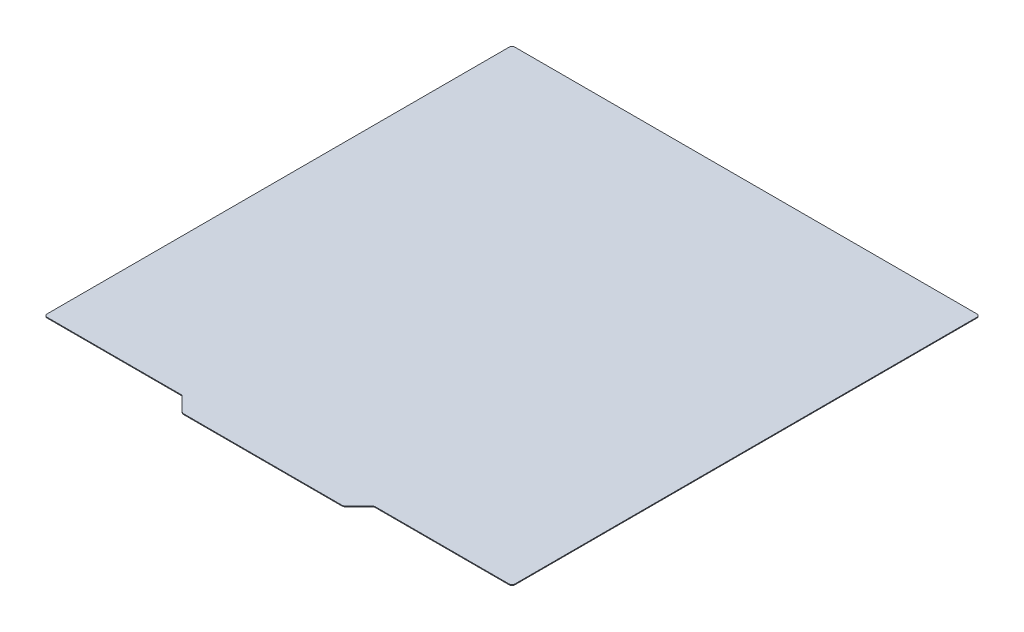
SolidWorks part; units mm, degrees
material "AISI Type 316L stainless steel"
ref_plane "Front Plane" through (0, 0, 0) normal (0, 0, 1) x (1, 0, 0)
ref_plane "Top Plane" through (0, 0, 0) normal (0, 1, 0) x (1, 0, 0)
ref_plane "Right Plane" through (0, 0, 0) normal (1, 0, 0) x (0, 0, -1)
sketch "Sketch1" plane through (0, 0, 0) normal (0, 1, 0) x (1, 0, 0)
  line L0 (-52.5, -162.5) -> (52.5, -162.5)
  line L1 (152.5, -152.5) -> (62.5, -152.5)
  line L2 (152.5, -152.5) -> (152.5, 152.5)
  line L3 (152.5, 152.5) -> (-152.5, 152.5)
  line L4 (-152.5, -152.5) -> (-152.5, 152.5)
  line L5 (152.5, -152.5) -> (-152.5, 152.5) construction
  line L6 (152.5, 152.5) -> (-152.5, -152.5) construction
  line L7 (52.5, -162.5) -> (62.5, -152.5)
  line L8 (-52.5, -162.5) -> (-62.5, -152.5)
  line L9 (-62.5, -152.5) -> (-152.5, -152.5)
  point P0 (0, 0)
  point P8 (0, -162.5)
  dimension "D1" = 305
  dimension "D2" = 10
  dimension "D3" = 105
extrude "Boss-Extrude1" add sketch "Sketch1" along normal blind 0.5
fillet "Fillet1" radius 2 8 edges at (-152.5, 0.25, -152.5) (152.5, 0.25, -152.5) (152.5, 0.25, 152.5) (62.5, 0.25, 152.5) (-52.5, 0.25, 162.5) (-62.5, 0.25, 152.5) (-152.5, 0.25, 152.5) (52.5, 0.25, 162.5)
